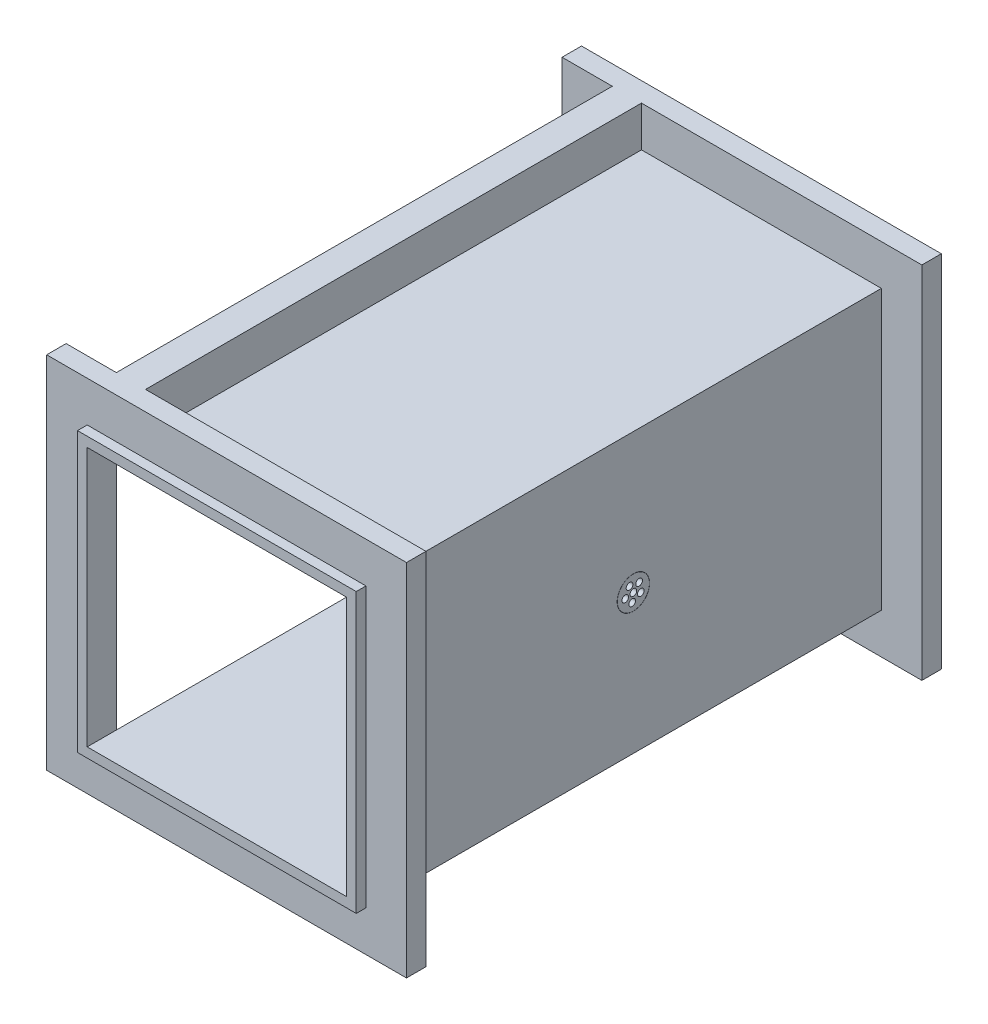
SolidWorks part; units mm, degrees
material "Teak"
ref_plane "Front Plane" through (0, 0, 0) normal (0, 0, 1) x (1, 0, 0)
ref_plane "Top Plane" through (0, 0, 0) normal (0, 1, 0) x (1, 0, 0)
ref_plane "Right Plane" through (0, 0, 0) normal (1, 0, 0) x (0, 0, -1)
sketch "Sketch1" plane through (0, 0, 0) normal (0, 0, 1) x (1, 0, 0)
  line L1 (80, -80) -> (-80, -80)
  line L2 (80, -80) -> (80, 80)
  line L3 (80, 80) -> (-80, 80)
  line L4 (-80, -80) -> (-80, 80)
  line L5 (80, -80) -> (-80, 80) construction
  line L6 (80, 80) -> (-80, -80) construction
  point P0 (0, 0)
  dimension "D1" = 160
extrude "Extrude-Thin1" add sketch "Sketch1" along normal blind 330 thin thin type one direction wall 6
sketch "Sketch5" plane through (0, 0, 330) normal (0, 0, 1) x (1, 0, 0)
  line L0 (0, 125.1227) -> (0, -114.1018) construction
  line L1 (-126.5771, 0) -> (116.9642, 0) construction
  line L12 (-80, -80) -> (80, -80) construction
  line L13 (80, -80) -> (80, 80) construction
  line L14 (80, 80) -> (-80, 80) construction
  line L15 (-80, 80) -> (-80, -80) construction
  line L20 (111, -111) -> (111, 111)
  line L21 (-111, -111) -> (111, -111)
  line L22 (-111, 111) -> (-111, -111)
  line L23 (111, 111) -> (-111, 111)
  line L24 (-80, -80) -> (80, -80)
  line L25 (80, -80) -> (80, 80)
  line L26 (80, 80) -> (-80, 80)
  line L27 (-80, 80) -> (-80, -80)
  point P6 (0, 111)
  point P9 (111, 0)
  dimension "D1" = 222
extrude "Boss-Extrude2" add sketch "Sketch5" against normal blind 12
ref_plane "Plane1" through (0, 0, 165) normal (0, 0, 1) x (1, 0, 0)
mirror "Mirror2" about plane through (0, 0, 165) normal (0, 0, 1) of "Boss-Extrude2"
sketch "Sketch6" plane through (0, 0, 0) normal (0, 0, -1) x (-1, 0, 0)
  line L0 (80, -80) -> (-80, -80) construction
  line L1 (80, 80) -> (80, -80) construction
  line L2 (-80, -80) -> (-80, 80) construction
  line L3 (-80, 80) -> (80, 80) construction
  line L4 (80, -80) -> (-80, -80)
  line L5 (80, 80) -> (80, -80)
  line L6 (-80, -80) -> (-80, 80)
  line L7 (-80, 80) -> (80, 80)
extrude "Extrude-Thin2" add sketch "Sketch6" along normal blind 6 thin thin type one direction wall 6
mirror "Mirror3" about plane through (0, 0, 165) normal (0, 0, 1) of "Extrude-Thin2"
sketch "Sketch7" plane through (0, 86, 0) normal (0, 1, 0) x (1, 0, 0)
  line L1 (-86, -12) -> (-80, -12)
  line L2 (-86, -12) -> (-86, -318)
  line L3 (-86, -318) -> (-80, -318)
  line L4 (-80, -12) -> (-80, -318)
  line L7 (86, -318) -> (86, -12) construction
  line L8 (86, -165) -> (-132.2167, -165) construction
  line L12 (-86, -318) -> (-86, -12) construction
  point P6 (-80, -165)
  dimension "D1" = 6
  dimension "D2" = 306
extrude "Cut-Extrude1" cut sketch "Sketch7" against normal through all
sketch "Sketch8" plane through (0, 86, 0) normal (0, 1, 0) x (1, 0, 0)
  line L0 (-80, -12) -> (86, -12) construction
  line L5 (-80, -12) -> (-62, -12)
  line L6 (-80, -12) -> (-80, -318)
  line L7 (-80, -318) -> (-62, -318)
  line L8 (-62, -12) -> (-62, -318)
  line L9 (111, -318) -> (-111, -318) construction
  line L10 (-80, -318) -> (-80, -12) construction
  dimension "D1" = 18
extrude "Boss-Extrude3" add sketch "Sketch8" along normal blind 25
mirror "Mirror7" about plane through (0, 0, 0) normal (0, 1, 0) of "Boss-Extrude3"
sketch "Sketch10" plane through (86, 0, 0) normal (1, 0, 0) x (0, 0, -1)
  circle A0 centre (-165, 0) radius 10
  circle A1 centre (-161.4485, 3.6601) radius 2.05
  circle A2 centre (-165, 0) radius 2.05
  circle A3 centre (-160.4215, -2.2467) radius 2.05
  circle A4 centre (-165.7219, -5.0487) radius 2.05
  circle A5 centre (-170.0246, -0.8736) radius 2.05
  circle A6 centre (-167.3835, 4.5088) radius 2.05
  circle A7 centre (-165, 0) radius 9.9
  point P16 (-165, 0)
  dimension "D1" = 20
  dimension "D2" = 4.1
  dimension "D3" = 5.1
  dimension "D5" = 0.1
  dimension "D4" = 5
extrude "Cut-Extrude2" cut sketch "Sketch10" against normal through all contours A6 | A1 | A2 | A5 | A4 | A3 | A0 A7
sketch "Sketch11" plane through (0, -80, 0) normal (0, 1, 0) x (1, 0, 0)
  line L0 (80, -336) -> (-80, -336) construction
  line L1 (-6, -185) -> (6, -185)
  line L2 (-6, -185) -> (-6, -145)
  line L3 (-6, -145) -> (6, -145)
  line L4 (6, -185) -> (6, -145)
  line L5 (-6, -185) -> (6, -145) construction
  line L6 (-6, -145) -> (6, -185) construction
  line L7 (-80, -318) -> (-80, -12) construction
  line L8 (-86, 6) -> (86, 6) construction
  line L9 (0, -165) -> (0, -6.0566) construction
  circle A0 centre (-15, -29) radius 10
  circle A1 centre (0, -195) radius 3
  circle A2 centre (15, -29) radius 10
  point P0 (0, -165)
  point P7 (0, -336)
  point P10 (-80, -165)
  point P13 (0, -145)
  point P19 (0, -185)
  dimension "D3" = 20
  dimension "D6" = 6
  dimension "D1" = 12
  dimension "D2" = 40
  dimension "D4" = 15
  dimension "D5" = 35
  dimension "D7" = 10
extrude "Cut-Extrude3" cut sketch "Sketch11" against normal blind 79
